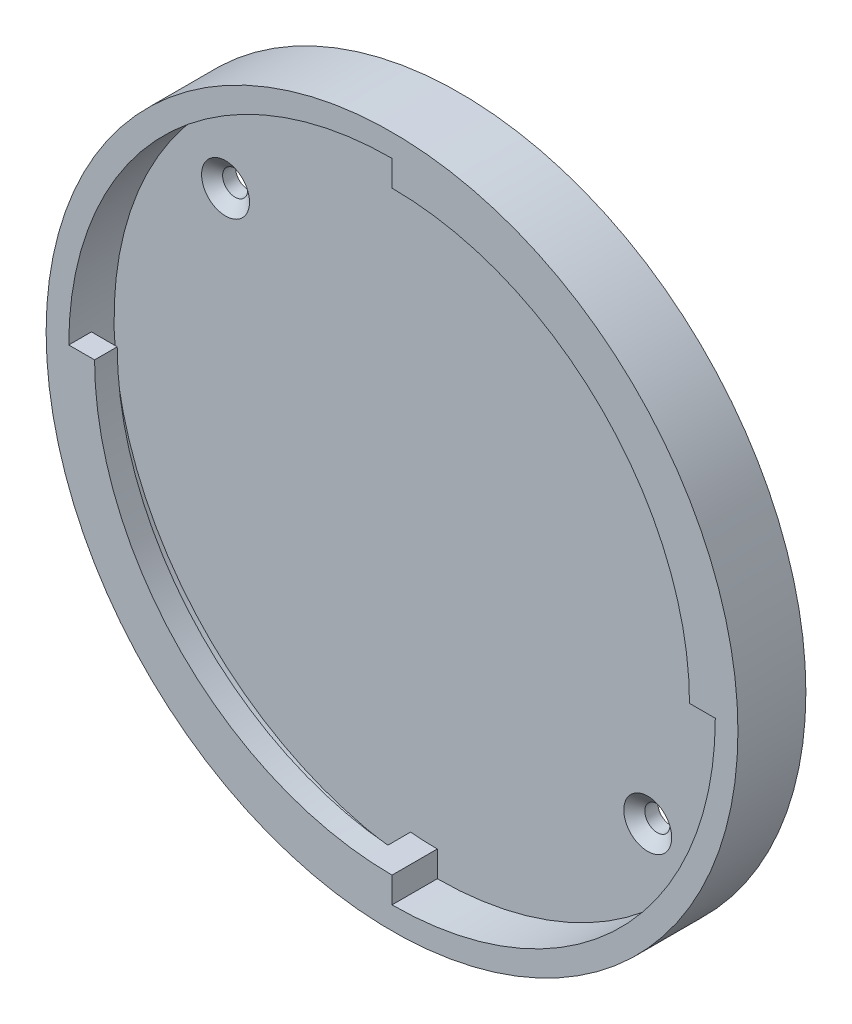
SolidWorks part; units mm, degrees
ref_plane "Front Plane" through (0, 0, 0) normal (0, 0, 1) x (1, 0, 0)
ref_plane "Top Plane" through (0, 0, 0) normal (0, 1, 0) x (1, 0, 0)
ref_plane "Right Plane" through (0, 0, 0) normal (1, 0, 0) x (0, 0, -1)
sketch "Sketch1" plane through (0, 0, 0) normal (0, 1, 0) x (1, 0, 0)
  line L0 (0, 0) -> (-116.3994, 0)
  line L1 (-116.3994, 0) -> (-116.3994, -6.35)
  line L2 (-108.7794, -7.62) -> (0, -7.62)
  line L3 (0, -7.62) -> (0, 0)
  line L6 (-116.3994, -6.35) -> (-116.3994, -22.86)
  line L7 (-116.3994, -22.86) -> (-109.8255, -22.86)
  line L8 (-108.7794, -7.62) -> (-108.7794, -15.24)
  line L9 (-109.8255, -22.86) -> (-100.0969, -22.86)
  line L11 (-108.7794, -15.24) -> (-100.0969, -15.24)
  line L12 (-100.0969, -22.86) -> (-100.0969, -15.24)
  dimension "D1" = 116.3994
  dimension "D2" = 6.35
  dimension "D3" = 7.62
  dimension "D4" = 7.62
  dimension "D5" = 7.62
  dimension "D6" = 7.62
revolve "Revolve1" add sketch "Sketch1" angle 360 about L3
sketch "Sketch2" plane through (0, 0, 22.86) normal (0, 0, 1) x (1, 0, 0)
  line L0 (0, 0) -> (-116.3994, 0) construction
  line L1 (-116.3994, 0) -> (0, 116.3994) construction
  line L2 (0, 116.3994) -> (0, -116.3994) construction
  line L3 (0, -116.3994) -> (116.3994, 0) construction
  line L4 (116.3994, 0) -> (0, 116.3994) construction
  line L5 (-116.3994, 0) -> (0, -116.3994) construction
  line L6 (0, 0) -> (116.3994, 0) construction
  line L7 (-116.3994, 0) -> (-108.7794, 0) construction
  line L8 (0, 116.3994) -> (0, 108.7794) construction
  line L9 (116.3994, 0) -> (108.7794, 0) construction
  line L10 (0, -116.3994) -> (0, -108.7794) construction
  line L11 (-108.7794, 0) -> (-14.77, 0)
  line L12 (-14.77, 0) -> (0, 14.77)
  line L13 (0, 14.77) -> (0, 108.7794)
  line L14 (0, -108.7794) -> (0, -24.8599)
  line L15 (0, -24.8599) -> (26.6579, 0)
  line L16 (26.6579, 0) -> (108.7794, 0)
  circle A0 centre (0, 0) radius 116.3994 construction
  arc A1 (0, -108.7794) -> (108.7794, 0) centre (0, 0) ccw
  arc A2 (0, 108.7794) -> (-108.7794, 0) centre (0, 0) ccw
  dimension "D2" = 7.62
  dimension "D3" = 7.62
extrude "Cut-Extrude1" cut sketch "Sketch2" against normal blind 12.7
sketch "Sketch4" plane through (0, 0, 7.62) normal (0, 0, 1) x (1, 0, 0)
  line L0 (0, 108.7794) -> (0, 100.0969)
  line L1 (0, 100.0969) -> (0, 108.7794) construction
  line L2 (0, -100.0969) -> (0, -108.7794)
  line L3 (0, 0) -> (9.0063, 99.6909) construction
  line L4 (9.0063, 99.6909) -> (-9.0063, -99.6909) construction
  line L5 (9.0063, 99.6909) -> (9.0063, 108.406)
  line L6 (-9.0063, -99.6909) -> (-9.0063, -108.406)
  arc A0 (9.0063, 108.406) -> (0, 108.7794) centre (0, 0) ccw
  arc A1 (-9.0063, -99.6909) -> (0, -100.0969) centre (0, 0) ccw
  arc A2 (9.0063, 99.6909) -> (0, 100.0969) centre (0, 0) ccw
  arc A3 (-9.0063, -108.406) -> (0, -108.7794) centre (0, 0) ccw
extrude "Boss-Extrude1" add sketch "Sketch4" along normal blind 12.7
hole_wizard "CSK for 5/16 Flat Head Machine Screw (100)1" positions "3DSketch2" profile "Sketch6" countersink size "5/16" standard "ANSI Inch" end condition through all
sketch3d "3DSketch2"
  point P0 (-71.2653, 56.7844, 7.62)
  point P2 (70.8072, -57.3546, 7.62)
  dimension "D1" = 91.44
  dimension "D2" = 91.44
sketch "Sketch6" plane through (-71.2653, 56.7844, 7.62) normal (1, 0, 0) x (0, -1, 0)
  line L0 (0, 0) -> (0, 7.62)
  line L1 (0, 7.62) -> (4.2164, 7.62)
  line L2 (4.2164, 7.62) -> (4.2164, 3.2289)
  line L3 (4.2164, 3.2289) -> (8.0645, 0)
  line L5 (8.0645, 0) -> (0, 0)
  line L6 (-4.2164, 3.2289) -> (-8.0645, 0) construction
  line L11 (0, -6.35) -> (0, 107.95) construction
  dimension "Thru Hole Dia." = 8.4328
  dimension "Thru Hole Depth" = 7.62
  dimension "Near C'Sink Dia." = 16.129
  dimension "Near C'Sink Angle" = 100
